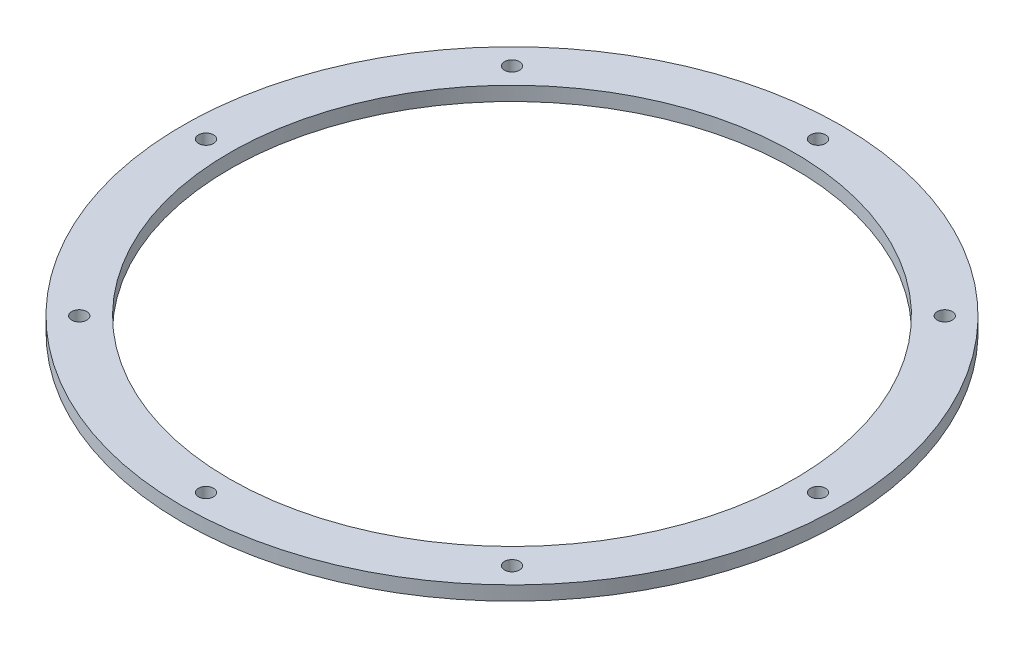
SolidWorks part; units mm, degrees
ref_plane "Front Plane" through (0, 0, 0) normal (0, 0, 1) x (1, 0, 0)
ref_plane "Top Plane" through (0, 0, 0) normal (0, 1, 0) x (1, 0, 0)
ref_plane "Right Plane" through (0, 0, 0) normal (1, 0, 0) x (0, 0, -1)
sketch "Sketch1" plane through (0, 0, 0) normal (0, 1, 0) x (1, 0, 0)
  circle A1 centre (0, 0) radius 60
  circle A2 centre (0, 0) radius 65 construction
  circle A3 centre (0, 0) radius 70
  circle A4 centre (0, 65) radius 1.6
  circle A5 centre (45.9619, 45.9619) radius 1.6
  circle A6 centre (65, 0) radius 1.6
  circle A7 centre (45.9619, -45.9619) radius 1.6
  circle A8 centre (0, -65) radius 1.6
  circle A9 centre (-45.9619, -45.9619) radius 1.6
  circle A10 centre (-65, 0) radius 1.6
  circle A11 centre (-45.9619, 45.9619) radius 1.6
  point P9 (0, 0)
  point P10 (45.9619, 45.9619)
  point P24 (0, 0)
  dimension "D1" = 120
  dimension "D2" = 5
  dimension "D3" = 5
  dimension "D4" = 3.2
  dimension "D5" = 8
extrude "Boss-Extrude1" add sketch "Sketch1" along normal blind 3
